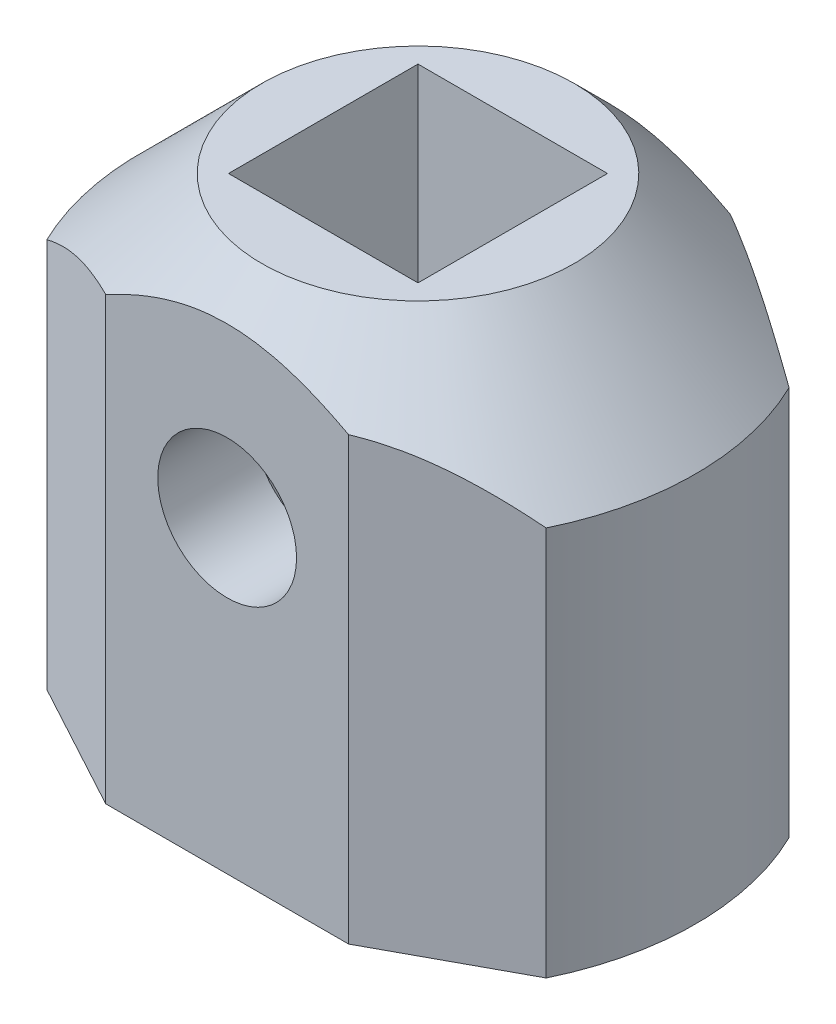
SolidWorks part; units mm, degrees
ref_plane "Front Plane" through (0, 0, 0) normal (0, 0, 1) x (1, 0, 0)
ref_plane "Top Plane" through (0, 0, 0) normal (0, 1, 0) x (1, 0, 0)
ref_plane "Right Plane" through (0, 0, 0) normal (1, 0, 0) x (0, 0, -1)
sketch "Sketch1" plane through (0, 0, 0) normal (0, 0, 1) x (1, 0, 0)
  line L0 (0, 0) -> (0, 29.464) construction
  line L1 (0, 29.464) -> (9, 29.464) construction
  line L2 (9, 29.464) -> (16, 22.464)
  line L3 (16, 22.464) -> (16, 0)
  line L4 (16, 0) -> (4.925, 0)
  line L5 (4.925, 0) -> (4.925, 29.464)
  line L6 (4.925, 29.464) -> (9, 29.464)
  line L7 (0, 0) -> (4.925, 0) construction
  dimension "D1" = 45
  dimension "D2" = 32
  dimension "D3" = 29.464
  dimension "D4" = 7
  dimension "D5" = 9.85
revolve "Revolve1" add sketch "Sketch1" angle 360 about L0
sketch "Sketch2" plane through (0, 0, 0) normal (0, 1, 0) x (1, 0, 0)
  line L0 (0, 0) -> (0, 11) construction
  line L1 (-7, 11) -> (7, 11)
  line L2 (7, 11) -> (14.3875, 7)
  line L3 (-7, 11) -> (-14.3875, 7)
  line L4 (0, 0) -> (-16, 0) construction
  line L5 (-7, -11) -> (-14.3875, -7)
  line L6 (7, -11) -> (14.3875, -7)
  line L7 (-7, -11) -> (7, -11)
  circle A0 centre (0, 0) radius 16 construction
  arc A1 (14.3875, 7) -> (-14.3875, 7) centre (0, 0) ccw
  arc A2 (14.3875, -7) -> (-14.3875, -7) centre (0, 0) cw
  dimension "D1" = 11
  dimension "D2" = 7
  dimension "D3" = 7
extrude "Cut-Extrude4" cut sketch "Sketch2" along normal through all contours L2 A1 L3 L1 | A2 L6 L7 L5
sketch "Sketch3" plane through (0, 0, 0) normal (0, 0, 1) x (1, 0, 0)
  line L0 (0, 17.78) -> (0, 0) construction
  circle A0 centre (0, 17.78) radius 4
  dimension "D1" = 8
  dimension "D2" = 17.78
extrude "Cut-Extrude5" cut sketch "Sketch3" against normal through all both and the other way through all
sketch "Sketch4" plane through (0, 0, 0) normal (0, -1, 0) x (1, 0, 0)
  line L1 (-5.461, 5.461) -> (5.461, 5.461)
  line L2 (-5.461, 5.461) -> (-5.461, -5.461)
  line L3 (-5.461, -5.461) -> (5.461, -5.461)
  line L4 (5.461, 5.461) -> (5.461, -5.461)
  line L5 (-5.461, 5.461) -> (5.461, -5.461) construction
  line L6 (-5.461, -5.461) -> (5.461, 5.461) construction
  point P0 (0, 0)
  dimension "D1" = 10.922
extrude "Cut-Extrude6" cut sketch "Sketch4" against normal through all
